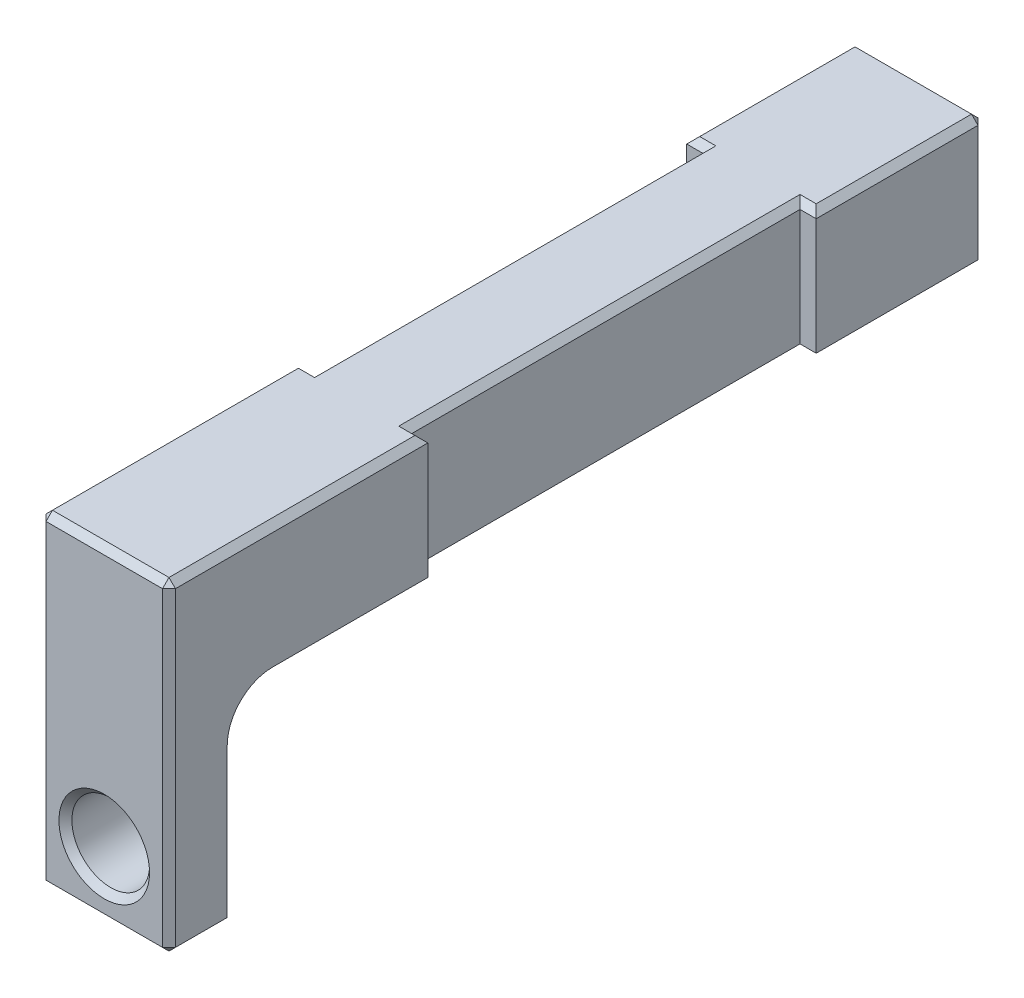
SolidWorks part; units mm, degrees
material "K110"
ref_plane "Front Plane" through (0, 0, 0) normal (0, 0, 1) x (1, 0, 0)
ref_plane "Top Plane" through (0, 0, 0) normal (0, 1, 0) x (1, 0, 0)
ref_plane "Right Plane" through (0, 0, 0) normal (1, 0, 0) x (0, 0, -1)
sketch "Sketch1" plane through (0, 0, 0) normal (0, 1, 0) x (1, 0, 0)
  line L1 (-5, -29) -> (5, -29)
  line L2 (-5, -29) -> (-5, 29)
  line L3 (-5, 29) -> (5, 29)
  line L4 (5, -29) -> (5, 29)
  line L5 (-5, -29) -> (5, 29) construction
  line L6 (-5, 29) -> (5, -29) construction
  point P0 (0, 0)
  dimension "D1" = 58
  dimension "D2" = 10
extrude "Boss-Extrude1" add sketch "Sketch1" against normal blind 10
sketch "Sketch2" plane through (0, 0, 0) normal (0, 1, 0) x (1, 0, 0)
  line L7 (-5, 29) -> (-5, -29) construction
  line L8 (-5, -14) -> (-3.75, -14)
  line L9 (-5, -14) -> (-5, 16)
  line L10 (-5, 16) -> (-3.75, 16)
  line L11 (-3.75, -14) -> (-3.75, 16)
  line L12 (5, -29) -> (5, 29) construction
  line L13 (5, -14) -> (3.75, -14)
  line L14 (5, -14) -> (5, 16)
  line L15 (5, 16) -> (3.75, 16)
  line L16 (3.75, -14) -> (3.75, 16)
  line L18 (-5, -29) -> (5, -29) construction
  dimension "D1" = 7.5
  dimension "D3" = 15
  dimension "D4" = 30
extrude "Cut-Extrude1" cut sketch "Sketch2" against normal up to next
sketch "Sketch3" plane through (0, 0, 29) normal (0, 0, 1) x (1, 0, 0)
  line L0 (5, -10) -> (5, 0) construction
  line L1 (-5, 0) -> (5, 0)
  line L2 (-5, 0) -> (-5, -25)
  line L3 (-5, -25) -> (5, -25)
  line L4 (5, 0) -> (5, -25)
  dimension "D1" = 25
extrude "Boss-Extrude2" add sketch "Sketch3" along normal blind 5
fillet "Fillet1" radius 3 1 edges at (0, -10, 29)
hole_wizard "M5 Clearance Hole1" positions "Sketch7" profile "Sketch5" hole size "M5" standard "ISO" end condition through all
sketch "Sketch7" plane through (0, 0, 34) normal (0, 0, 1) x (1, 0, 0)
  line L0 (-5, -25) -> (5, -25) construction
  point P0 (0, -20)
  dimension "D1" = 5
sketch "Sketch5" plane through (0, -20, 34) normal (1, 0, 0) x (0, -1, 0)
  line L0 (0, 0) -> (0, 63)
  line L1 (0, 63) -> (3, 63)
  line L2 (3, 63) -> (3, 0)
  line L5 (3, 0) -> (0, 0)
  line L11 (0, -6.35) -> (0, 107.95) construction
  dimension "Thru Hole Dia." = 6
  dimension "Thru Hole Depth" = 63
chamfer "Chamfer1" distance 0.5 angle 45 36 edges at (-5, -10, -22.5) (5, 0, -22.5) (-5, 0, 24) (5, -10, -22.5) (-5, -10, 20) (-4.375, -10, -16) (-3.75, -10, -1) (-4.375, -10, 14) (-4.375, 0, 14) (-3.75, 0, -1) (-4.375, 0, -16) (4.375, -10, 14) (3.75, -10, -1) (4.375, -10, -16) (4.375, 0, -16) (3.75, 0, -1) (4.375, 0, 14) (0, -25, 29) (-5, -25, 31.5) (5, -19, 29) (5, -25, 31.5) (-5, -12.5, 34) (0, -25, 34) (5, -12.5, 34) (0, 0, 34) (-5, 0, -22.5) (0, 0, -29) (-5, -19, 29) (5, -10, 20) (5, -10.8787, 28.1213) (-5, -10.8787, 28.1213) (5, 0, 24) (3, -20, 34) (-5, -5, -29) (5, -5, -29) (0, -10, -29)
